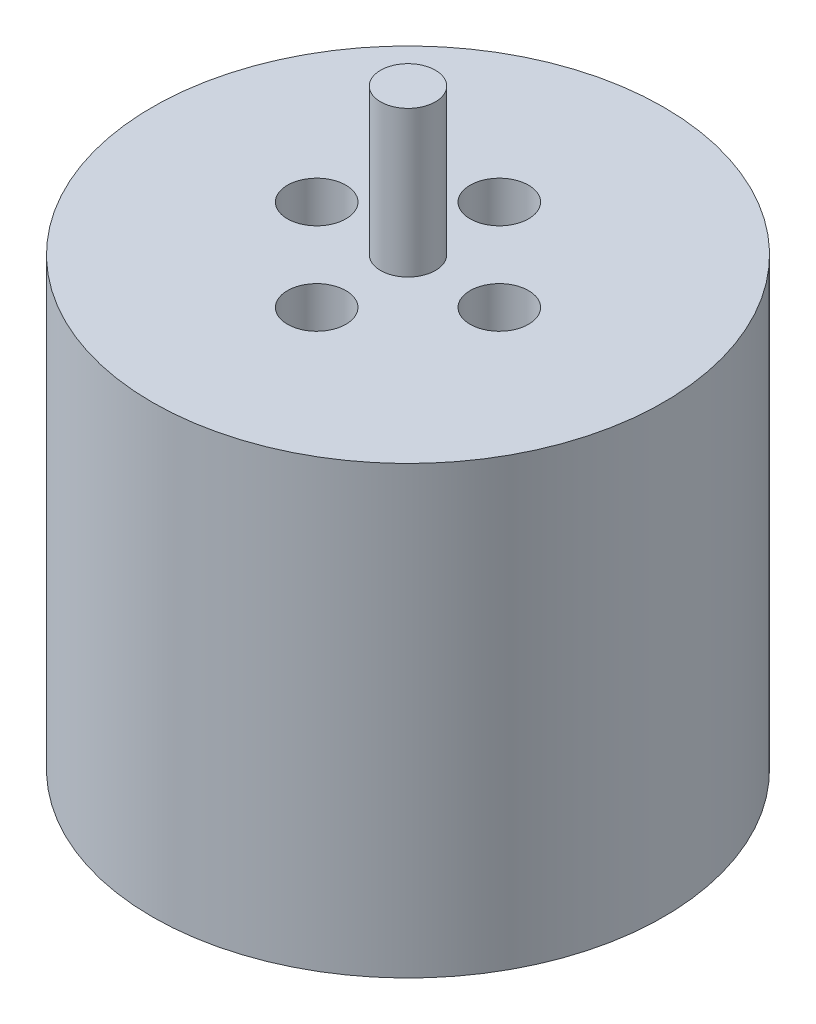
SolidWorks part; units mm, degrees
ref_plane "Front Plane" through (0, 0, 0) normal (0, 0, 1) x (1, 0, 0)
ref_plane "Top Plane" through (0, 0, 0) normal (0, 1, 0) x (1, 0, 0)
ref_plane "Right Plane" through (0, 0, 0) normal (1, 0, 0) x (0, 0, -1)
sketch "Sketch1" plane through (0, 0, 0) normal (0, 1, 0) x (1, 0, 0)
  circle A0 centre (0, 0) radius 7
  dimension "D1" = 14
extrude "Boss-Extrude1" add sketch "Sketch1" along normal mid plane 12.2
sketch "Sketch2" plane through (0, -6.1, 0) normal (0, -1, 0) x (1, 0, 0)
  circle A0 centre (0, 0) radius 0.75
  dimension "D1" = 1.5
extrude "Boss-Extrude2" add sketch "Sketch2" along normal blind 1
sketch "Sketch3" plane through (0, 6.1, 0) normal (0, 1, 0) x (1, 0, 0)
  circle A0 centre (0, 0) radius 0.75
  dimension "D1" = 1.5
extrude "Boss-Extrude3" add sketch "Sketch3" along normal blind 4
sketch "Sketch4" plane through (0, -6.1, 0) normal (0, -1, 0) x (1, 0, 0)
  circle A0 centre (0, 4.5) radius 0.8
  circle A1 centre (4.5, 0) radius 0.8
  circle A2 centre (0, -4.5) radius 0.8
  circle A3 centre (-4.5, 0) radius 0.8
  point P8 (0, 0)
  point P11 (0, 0)
  dimension "D1" = 1.6
  dimension "D2" = 9
  dimension "D3" = 9
  dimension "D4" = 4.5
  dimension "D5" = 4.5
extrude "Cut-Extrude1" cut sketch "Sketch4" against normal blind 2
sketch "Sketch5" plane through (0, 6.1, 0) normal (0, 1, 0) x (1, 0, 0)
  circle A0 centre (2.5, 0) radius 0.8
  circle A1 centre (0, -2.5) radius 0.8
  circle A2 centre (-2.5, 0) radius 0.8
  circle A3 centre (0, 2.5) radius 0.8
  circle A4 centre (0, 0) radius 2.5 construction
  point P8 (0, 0)
  point P10 (0, 0)
  point P11 (0, 0)
  point P14 (0, 0)
  point P15 (0, 0)
  dimension "D1" = 1.6
  dimension "D2" = 5
extrude "Cut-Extrude2" cut sketch "Sketch5" against normal blind 2
equation "\"D3@Sketch4\"=\"D2@Sketch4\""
equation "\"D4@Sketch4\"=\"D2@Sketch4\"/2"
equation "\"D5@Sketch4\"=\"D4@Sketch4\""
